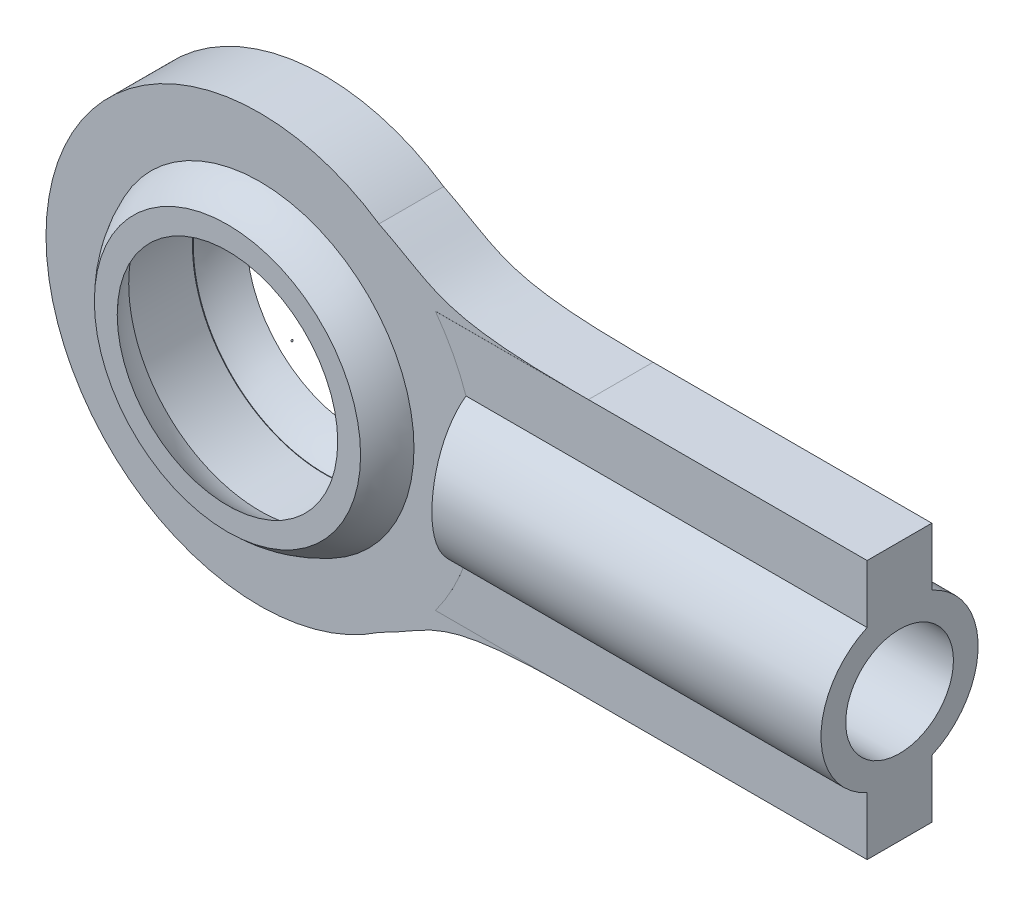
SolidWorks part; units mm, degrees
ref_plane "Front Plane" through (0, 0, 0) normal (0, 0, 1) x (1, 0, 0)
ref_plane "Top Plane" through (0, 0, 0) normal (0, 1, 0) x (1, 0, 0)
ref_plane "Right Plane" through (0, 0, 0) normal (1, 0, 0) x (0, 0, -1)
sketch "Sketch1" plane through (0, 0, 0) normal (0, 0, 1) x (1, 0, 0)
  line L1 (37.5598, -8.0097) -> (37.5598, 8.0097)
  line L2 (37.5598, -8.0097) -> (20.3264, -8.0097)
  line L3 (37.5598, 8.0097) -> (20.3264, 8.0097)
  arc A0 (7.3721, 10.9375) -> (7.3721, -10.9375) centre (-0.017, 0) ccw
  spline S0 degree 3 poles (7.3721, 10.9375) (11.0593, 9.1124) (10.9361, 7.9609) (20.3264, 8.0097) knots 0 0 0 0 1 1 1 1
  spline S1 degree 3 poles (7.3721, -10.9375) (11.0593, -9.1124) (10.9361, -7.9609) (20.3264, -8.0097) knots 0 0 0 0 1 1 1 1
  point P4 (-7.3721, 10.9375)
  point P16 (-13.19, 0)
extrude "Boss-Extrude3" add sketch "Sketch1" along normal blind 10
sketch "Sketch2" plane through (0, 0, 10) normal (0, 0, 1) x (1, 0, 0)
  circle A0 centre (0, 0) radius 13.5
extrude "Cut-Extrude1" cut sketch "Sketch2" against normal blind 3
sketch "Sketch3" plane through (0, 0, 0) normal (0, 0, -1) x (-1, 0, 0)
  circle A0 centre (0, 0) radius 13.5
extrude "Cut-Extrude2" cut sketch "Sketch3" against normal blind 3
ref_plane "Plane1" through (0, 0, 5) normal (0, 0, 1) x (1, 0, 0)
sketch "Sketch4" plane through (0, 0, 7) normal (0, 0, 1) x (1, 0, 0)
  circle A0 centre (-0.017, 0) radius 7.69
sketch "Sketch7" plane through (37.5598, 0, 0) normal (1, 0, 0) x (0, 0, -1)
  line L0 (-7.0041, -8.0097) -> (-10, -8.0097)
  line L1 (-10, 8.0097) -> (-7.0041, 8.0097)
  line L2 (0, 8.0097) -> (-3.0037, 8.0097)
  line L3 (-7.0041, -4.42) -> (-7.0041, -8.0097)
  line L4 (0, 8.0097) -> (0, -8.0097)
  line L5 (0, -8.0097) -> (-3.0037, -8.0097)
  line L6 (-10, 8.0097) -> (-10, -8.0097)
  line L7 (-3.0037, 8.0097) -> (-3.0037, 4.4235)
  line L8 (0, 0) -> (-10, 0) construction
  line L9 (-7.0041, 8.0097) -> (-7.0041, 4.42)
  line L10 (-3.0037, -4.4235) -> (-3.0037, -8.0097)
  arc A0 (-3.0037, 4.4235) -> (-3.0037, -4.4235) centre (-4.9869, 0) cw
  arc A1 (-7.0041, 4.42) -> (-7.0041, -4.42) centre (-5.0043, 0) ccw
  point P0 (-0.1533, 0)
  point P2 (-9.8467, 0)
  point P15 (-3.0037, 4.4235)
  point P17 (-7.0041, 4.42)
  point P19 (-7.0041, -4.42)
  point P21 (-3.0037, -4.4235)
extrude "Cut-Extrude5" cut sketch "Sketch7" against normal blind 29 from surface at 0 starting at face at (37.5598, 0, 5)
sketch "Sketch9" plane through (0, 0, 0) normal (1, 0, 0) x (0, 0, -1)
  line L0 (-7, 10.0578) -> (-10, 10.0578)
  line L1 (-10, 10.0578) -> (-10, 8.0097)
  line L2 (-10, 8.0097) -> (-7, 8.0097)
  line L3 (-7, 8.0097) -> (-7, 10.0578)
  line L4 (-7, -8.0097) -> (-10, -8.0097)
  line L5 (-10, -8.0097) -> (-10, -10.0578)
  line L6 (-10, -10.0578) -> (-7, -10.0578)
  line L7 (-7, -10.0578) -> (-7, -8.0097)
  line L8 (-3, 10.0578) -> (0, 10.0578)
  line L9 (0, 10.0578) -> (0, 8.0097)
  line L10 (0, 8.0097) -> (-3, 8.0097)
  line L11 (-3, 8.0097) -> (-3, 10.0578)
  line L12 (-3, -10.0578) -> (0, -10.0578)
  line L13 (0, -10.0578) -> (0, -8.0097)
  line L14 (0, -8.0097) -> (-3, -8.0097)
  line L15 (-3, -8.0097) -> (-3, -10.0578)
extrude "Cut-Extrude6" cut sketch "Sketch9" along normal through all
sketch "Sketch14" plane through (37.5598, 0, 0) normal (1, 0, 0) x (0, 0, -1)
  line L0 (-0.1392, 0) -> (-9.8557, 0) construction
  circle A0 centre (-4.9974, 0) radius 3.33
extrude "Cut-Extrude11" cut sketch "Sketch14" against normal blind 24
sketch "Sketch15" plane through (0, 0, 0) normal (0, 1, 0) x (1, 0, 0)
  line L0 (0.0107, -9.0065) -> (0.0107, -0.9935) construction
  line L1 (0.0107, -0.9935) -> (-9.7193, -0.9935) construction
  line L2 (-0.0347, -14.3034) -> (-0.0119, -13.1987)
  line L3 (0.0107, -5) -> (-16.2706, -5) construction
  line L4 (0.0107, -9.0065) -> (-9.7193, -9.0065) construction
  line L5 (0.0107, -0.9935) -> (-6.8067, -0.9935) construction
  line L6 (0.0107, -9.0065) -> (-6.8067, -9.0065) construction
  line L7 (-9.7193, -0.9935) -> (-8.2209, -0.9935) construction
  line L8 (-9.7193, -9.0065) -> (-8.2209, -9.0065) construction
  line L9 (-6.8067, -0.9935) -> (-6.8067, -5) construction
  line L11 (-8.2209, -0.9935) -> (-6.8067, -0.9935)
  line L12 (-8.2209, -9.0065) -> (-6.8067, -9.0065)
  arc A0 (-8.2209, -0.9935) -> (-8.2209, -9.0065) centre (-4.2143, -5) ccw
  arc A1 (-6.8067, -0.9935) -> (-6.8067, -9.0065) centre (-2.8002, -5) ccw
revolve "Revolve5" add sketch "Sketch15" angle 360 about L0
sketch "Sketch16" plane through (0, 0, 3) normal (0, 0, -1) x (-1, 0, 0)
  circle A0 centre (0.017, 0) radius 8.1399
extrude "Cut-Extrude13" cut sketch "Sketch16" against normal up to surface (4 mm away) up to face at (9.4941, -0.488, 7)
sketch "Sketch18" plane through (0, 0, 5) normal (0, 0, 1) x (1, 0, 0)
  line L0 (0, 0.05) -> (0, -0.05)
  arc A0 (0, 0.05) -> (0, -0.05) centre (0, 0) ccw
revolve "Revolve7" add sketch "Sketch18" angle 360 about L0
